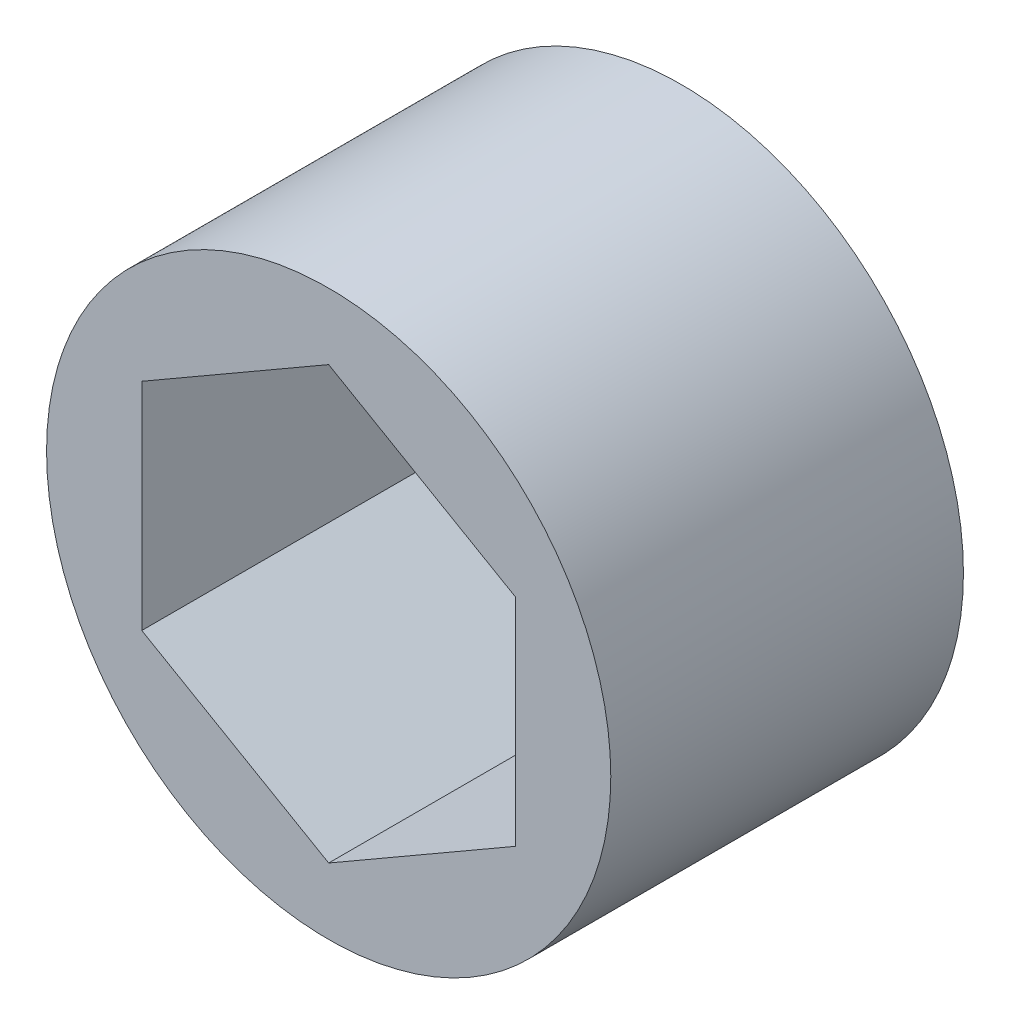
SolidWorks part; units mm, degrees
material "Nylon 101"
ref_plane "Front Plane" through (0, 0, 0) normal (0, 0, 1) x (1, 0, 0)
ref_plane "Top Plane" through (0, 0, 0) normal (0, 1, 0) x (1, 0, 0)
ref_plane "Right Plane" through (0, 0, 0) normal (1, 0, 0) x (0, 0, -1)
sketch "Sketch1" plane through (0, 0, 0) normal (0, 0, 1) x (1, 0, 0)
  line L1 (0, 7.7723) -> (-6.731, 3.8861)
  line L2 (-6.731, 3.8861) -> (-6.731, -3.8861)
  line L3 (-6.731, -3.8861) -> (0, -7.7723)
  line L4 (0, -7.7723) -> (6.731, -3.8861)
  line L5 (6.731, -3.8861) -> (6.731, 3.8861)
  line L6 (6.731, 3.8861) -> (0, 7.7723)
  circle A0 centre (0, 0) radius 10.16
  circle A1 centre (0, 0) radius 6.731 construction
  point P3 (0, 0)
  dimension "D1" = 20.32
  dimension "D2" = 13.462
extrude "Boss-Extrude1" add sketch "Sketch1" along normal mid plane 12.7
